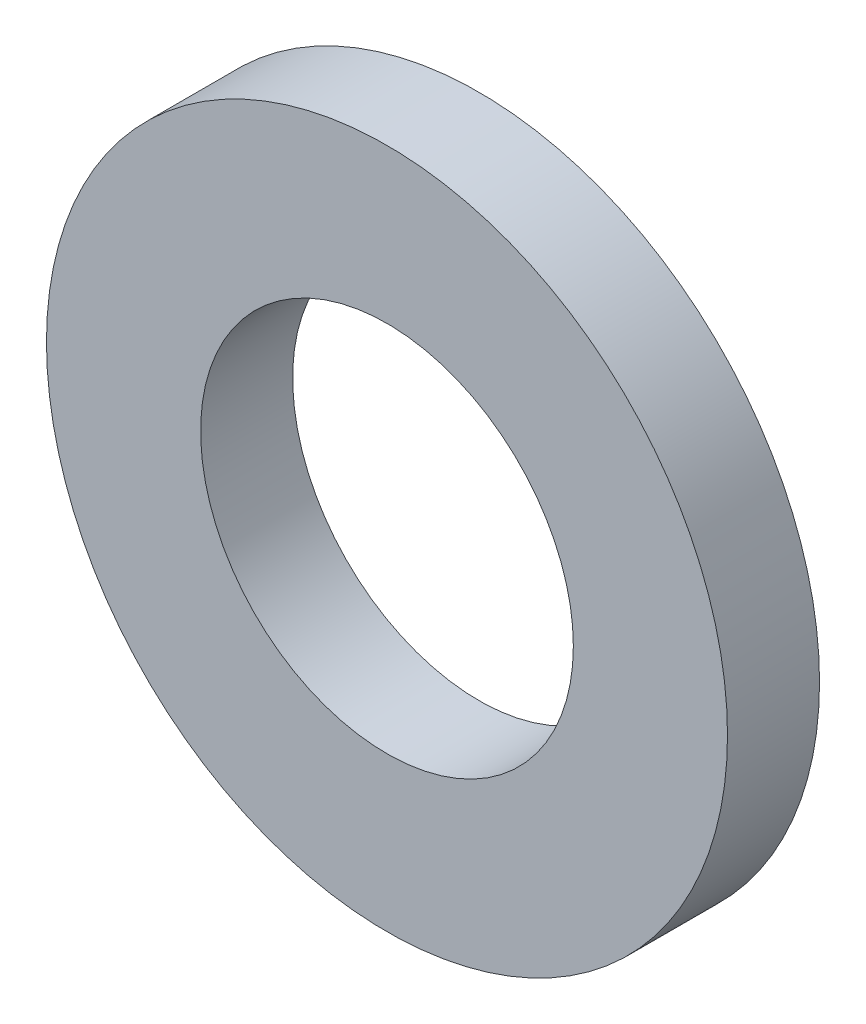
SolidWorks part; units mm, degrees
material "1.4301 (X5CrNi18-10)"
ref_plane "Спереди" through (0, 0, 0) normal (0, 0, 1) x (1, 0, 0)
ref_plane "Сверху" through (0, 0, 0) normal (0, 1, 0) x (1, 0, 0)
ref_plane "Справа" through (0, 0, 0) normal (1, 0, 0) x (0, 0, -1)
sketch "Эскиз1" plane through (0, 0, 0) normal (0, 0, 1) x (1, 0, 0)
  circle A0 centre (0, 0) radius 7.4
  circle A1 centre (0, 0) radius 4.05
  dimension "D1" = 8.1
  dimension "D2" = 14.8
extrude "Бобышка-Вытянуть1" add sketch "Эскиз1" along normal blind 2
